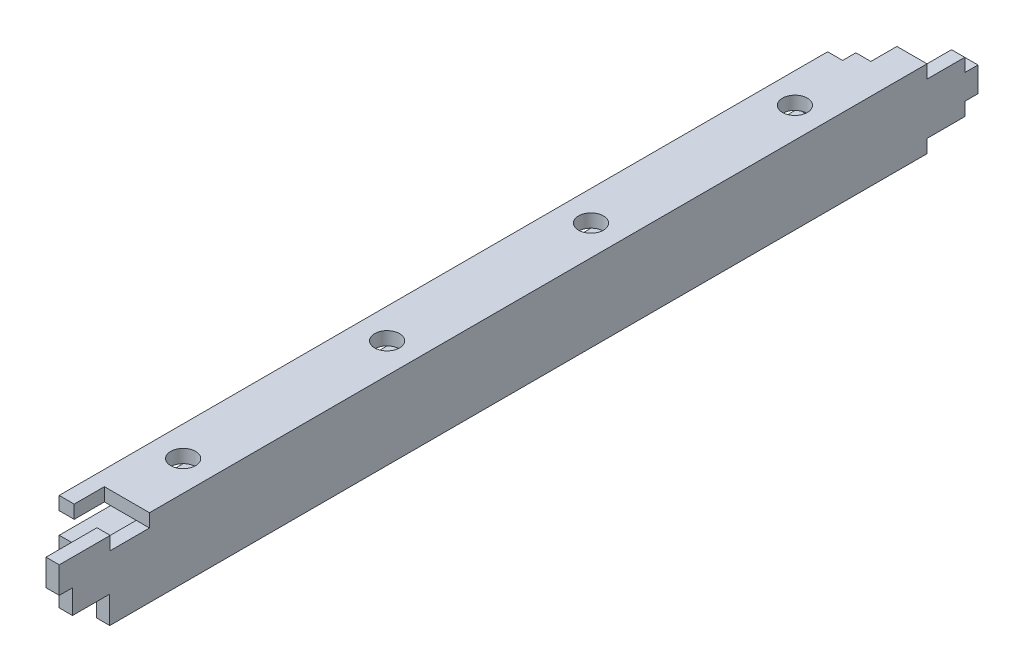
SolidWorks part; units mm, degrees
ref_plane "Front" through (0, 0, 0) normal (0, 0, 1) x (1, 0, 0)
ref_plane "Top" through (0, 0, 0) normal (0, 1, 0) x (1, 0, 0)
ref_plane "Right" through (0, 0, 0) normal (1, 0, 0) x (0, 0, -1)
sketch "Sketch1" plane through (0, 0, 0) normal (0, 0, 1) x (1, 0, 0)
  line L0 (0, 0) -> (11.24, 0)
  line L1 (11.24, 0) -> (11.24, 9.7)
  line L2 (11.24, 9.7) -> (0, 9.7)
  line L3 (0, 1.65) -> (0, 0)
  line L4 (0, 1.65) -> (9.59, 1.65)
  line L6 (9.59, 1.65) -> (9.59, 8.05)
  line L7 (9.59, 8.05) -> (0, 8.05)
  line L8 (0, 9.7) -> (0, 8.05)
extrude "Extrude4" add sketch "Sketch1" along normal blind 114.43
sketch "Sketch2" plane through (11.24, 0, 0) normal (1, 0, 0) x (0, 0, -1)
  line L0 (-6.35, 1.65) -> (-1.65, 1.65)
  line L1 (-6.35, 0) -> (0, 0)
  line L2 (0, 0) -> (0, 3.3)
  line L3 (0, 3.3) -> (-1.65, 3.3)
  line L4 (-6.35, 0) -> (-6.35, 1.65)
  line L5 (0, 9.7) -> (-6.35, 9.7)
  line L6 (0, 9.7) -> (0, 6.4)
  line L7 (0, 6.4) -> (-1.65, 6.4)
  line L8 (-1.65, 8.05) -> (-1.65, 6.4)
  line L9 (-114.43, 0) -> (0, 0) construction
  line L10 (-6.35, 9.7) -> (-6.35, 8.05)
  line L11 (-1.65, 1.65) -> (-1.65, 3.3)
  line L12 (-114.43, 9.7) -> (0, 9.7) construction
  line L13 (-6.35, 8.05) -> (-1.65, 8.05)
extrude "Cut-Extrude1" cut sketch "Sketch2" against normal through all
sketch "Sketch3" plane through (0, 9.7, 0) normal (0, 1, 0) x (-1, 0, 0)
  line L0 (0, 6.35) -> (0, 114.43)
  line L1 (-11.24, 103.19) -> (-11.24, 108.08)
  line L2 (-3.75, 11.24) -> (-5.62, 11.24)
  line L3 (-7.49, 9.59) -> (-5.62, 9.59)
  line L4 (-7.49, 9.59) -> (-7.49, 6.35)
  line L5 (-7.49, 6.35) -> (0, 6.35)
  line L6 (-5.62, 11.24) -> (-5.62, 9.59)
  line L7 (-3.75, 106.95) -> (-3.75, 11.24)
  line L8 (-11.24, 114.43) -> (-11.24, 6.35) construction
  line L9 (-9.59, 114.43) -> (0, 114.43)
  line L10 (-11.24, 114.43) -> (0, 114.43) construction
  line L12 (-11.24, 108.08) -> (-9.59, 108.08)
  line L13 (-9.59, 108.08) -> (-9.59, 114.43)
  line L14 (-5.62, 106.95) -> (-3.75, 106.95)
  line L15 (-11.24, 103.19) -> (-5.62, 103.19)
  line L16 (-5.62, 103.19) -> (-5.62, 106.95)
  circle A0 centre (-7.49, 19.05) radius 1.55
  circle A1 centre (-7.49, 44.45) radius 1.55
  circle A2 centre (-7.49, 69.85) radius 1.55
  circle A3 centre (-7.49, 95.25) radius 1.55
extrude "Cut-Extrude2" cut sketch "Sketch3" against normal blind 1.65
sketch "Sketch4" plane through (0, 0, 0) normal (0, -1, 0) x (1, 0, 0)
  line L0 (7.49, 6.35) -> (7.49, 9.2)
  line L1 (0, 6.35) -> (11.24, 6.35) construction
  line L2 (7.49, 9.2) -> (5.62, 9.2)
  line L3 (5.62, 9.2) -> (5.62, 11.24)
  line L4 (5.62, 11.24) -> (0, 11.24)
  line L5 (0, 11.24) -> (0, 6.35)
  line L6 (0, 6.35) -> (7.49, 6.35)
  line L7 (0, 103.19) -> (9.59, 103.19)
  line L8 (0, 114.43) -> (0, 6.35) construction
  line L9 (9.59, 103.19) -> (9.59, 104.84)
  line L10 (9.59, 104.84) -> (6.35, 104.84)
  line L11 (6.35, 104.84) -> (6.35, 106.49)
  line L12 (6.35, 106.49) -> (9.59, 106.49)
  line L13 (9.59, 106.49) -> (9.59, 108.14)
  line L14 (9.59, 108.14) -> (11.24, 108.14)
  line L15 (11.24, 114.43) -> (11.24, 6.35) construction
  line L16 (11.24, 114.43) -> (11.24, 108.14)
  line L17 (11.24, 114.43) -> (0, 114.43)
  line L18 (0, 114.43) -> (0, 103.19)
extrude "Cut-Extrude3" cut sketch "Sketch4" against normal blind 3.4
sketch "Sketch5" plane through (11.24, 0, 0) normal (1, 0, 0) x (0, 0, -1)
  line L0 (-114.43, 6.4) -> (-112.78, 6.4)
  line L1 (-114.43, 3.4) -> (-114.43, 9.7) construction
  line L2 (-112.78, 6.4) -> (-112.78, 3.4)
  line L3 (-108.14, 3.4) -> (-114.43, 3.4) construction
  line L4 (-114.43, 6.4) -> (-114.43, 3.4)
  line L5 (-112.78, 3.4) -> (-114.43, 3.4)
extrude "Cut-Extrude4" cut sketch "Sketch5" against normal blind 1.65
